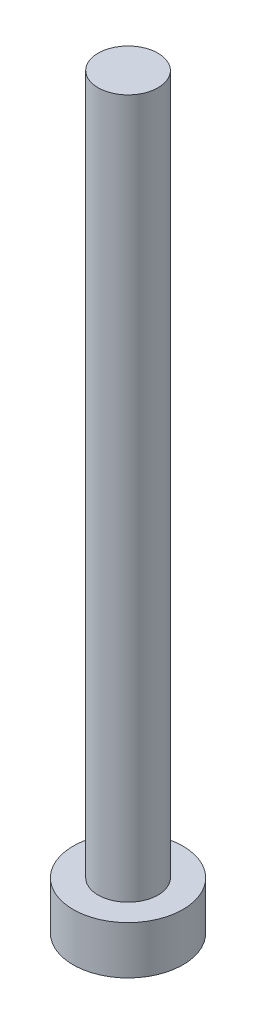
SolidWorks part; units mm, degrees
ref_plane "Front Plane" through (0, 0, 0) normal (0, 0, 1) x (1, 0, 0)
ref_plane "Top Plane" through (0, 0, 0) normal (0, 1, 0) x (1, 0, 0)
ref_plane "Right Plane" through (0, 0, 0) normal (1, 0, 0) x (0, 0, -1)
sketch "Sketch1" plane through (0, 0, 0) normal (1, 0, 0) x (0, 0, -1)
  line L0 (0, 0) -> (0, 35)
  line L1 (0, 35) -> (1.5, 35)
  line L2 (1.5, 35) -> (1.5, 0)
  line L3 (1.5, 0) -> (2.75, 0)
  line L4 (2.75, 0) -> (2.75, -2.4)
  line L5 (2.75, -2.4) -> (0, -2.4)
  line L6 (0, -2.4) -> (0, 0)
  line L7 (0, 0) -> (0, 42.8482) construction
  point P9 (0, 42.8482)
  dimension "D1" = 3
  dimension "D2" = 35
  dimension "D3" = 2.4
  dimension "D4" = 5.5
revolve "Revolve1" add sketch "Sketch1" angle 360 about L7
